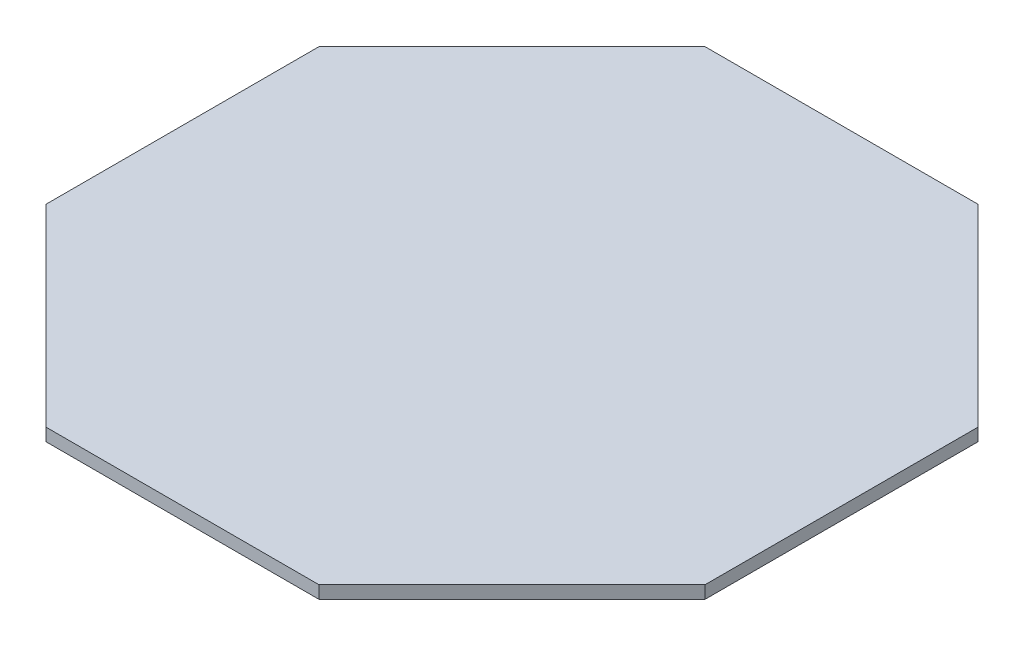
SolidWorks part; units mm, degrees
ref_plane "Front Plane" through (0, 0, 0) normal (0, 0, 1) x (1, 0, 0)
ref_plane "Top Plane" through (0, 0, 0) normal (0, 1, 0) x (1, 0, 0)
ref_plane "Right Plane" through (0, 0, 0) normal (1, 0, 0) x (0, 0, -1)
sketch "Sketch6" plane through (0, 0, 0) normal (0, 1, 0) x (1, 0, 0)
  line L1 (78, 32.3087) -> (32.3087, 78)
  line L2 (32.3087, 78) -> (-32.3087, 78)
  line L3 (-32.3087, 78) -> (-78, 32.3087)
  line L4 (-78, 32.3087) -> (-78, -32.3087)
  line L5 (-78, -32.3087) -> (-32.3087, -78)
  line L6 (-32.3087, -78) -> (32.3087, -78)
  line L7 (32.3087, -78) -> (78, -32.3087)
  line L8 (78, -32.3087) -> (78, 32.3087)
  circle A0 centre (0, 0) radius 78 construction
extrude "Boss-Extrude5" add sketch "Sketch6" against normal blind 3
sketch "Sketch9" plane through (0, 0, 0) normal (0, 1, 0) x (1, 0, 0)
  line L18 (75, -31.066) -> (75, 31.066)
  line L19 (75, 31.066) -> (31.066, 75)
  line L20 (31.066, 75) -> (-31.066, 75)
  line L21 (-31.066, 75) -> (-75, 31.066)
  line L22 (-75, 31.066) -> (-75, -31.066)
  line L23 (-75, -31.066) -> (-31.066, -75)
  line L24 (-31.066, -75) -> (31.066, -75)
  line L25 (31.066, -75) -> (75, -31.066)
  line L26 (75, -31.066) -> (75, 31.066) construction
  line L27 (75, 31.066) -> (31.066, 75) construction
  line L28 (31.066, 75) -> (-31.066, 75) construction
  line L29 (-31.066, 75) -> (-75, 31.066) construction
  line L30 (-75, 31.066) -> (-75, -31.066) construction
  line L31 (-75, -31.066) -> (-31.066, -75) construction
  line L32 (-31.066, -75) -> (31.066, -75) construction
  line L33 (31.066, -75) -> (75, -31.066) construction
  dimension "D1" = 3
